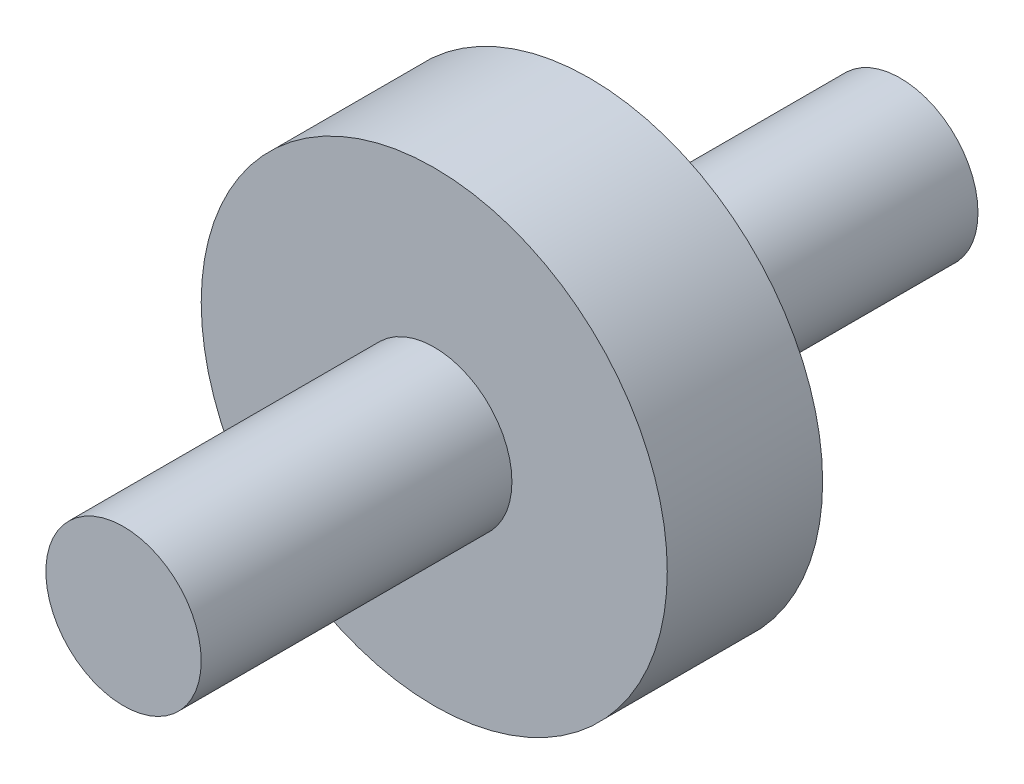
SolidWorks part; units mm, degrees
ref_plane "Plan de face" through (0, 0, 0) normal (0, 0, 1) x (1, 0, 0)
ref_plane "Plan de dessus" through (0, 0, 0) normal (0, 1, 0) x (1, 0, 0)
ref_plane "Plan de droite" through (0, 0, 0) normal (1, 0, 0) x (0, 0, -1)
sketch "Sketch1" plane through (0, 0, 0) normal (0, 0, 1) x (1, 0, 0)
  circle A0 centre (0, 0) radius 15
  dimension "D1" = 30
extrude "Boss-Extrude1" add sketch "Sketch1" along normal blind 10 contours A0
sketch "Sketch2" plane through (0, 0, 0) normal (0, 0, 1) x (1, 0, 0)
  circle A0 centre (0, 0) radius 5
  dimension "D1" = 10
extrude "Boss-Extrude2" add sketch "Sketch2" against normal blind 20 and the other way blind 30
